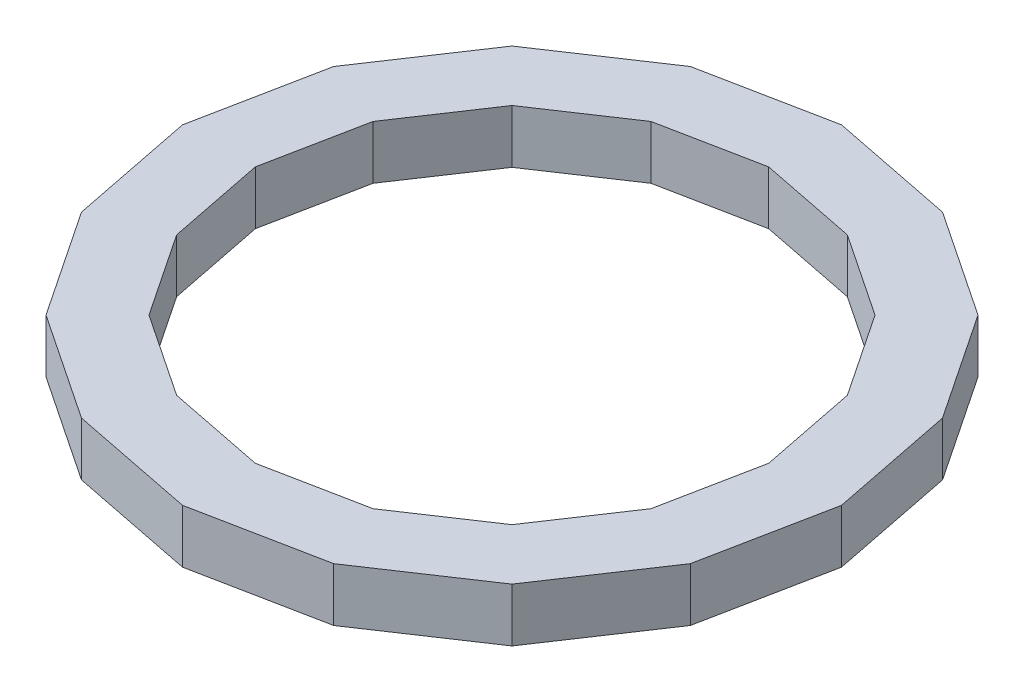
SolidWorks part; units mm, degrees
ref_plane "Front Plane" through (0, 0, 0) normal (0, 0, 1) x (1, 0, 0)
ref_plane "Top Plane" through (0, 0, 0) normal (0, 1, 0) x (1, 0, 0)
ref_plane "Right Plane" through (0, 0, 0) normal (1, 0, 0) x (0, 0, -1)
sketch "Sketch1" plane through (0, 0, 0) normal (0, 1, 0) x (1, 0, 0)
  line L0 (108.257, 44.8415) -> (84.3307, 34.9309) construction
  line L1 (117.1765, 0) -> (108.257, 44.8415)
  line L2 (108.257, 44.8415) -> (82.8563, 82.8563)
  line L3 (82.8563, 82.8563) -> (44.8415, 108.257)
  line L4 (44.8415, 108.257) -> (0, 117.1765)
  line L5 (0, 117.1765) -> (-44.8415, 108.257)
  line L6 (-44.8415, 108.257) -> (-82.8563, 82.8563)
  line L7 (-82.8563, 82.8563) -> (-108.257, 44.8415)
  line L8 (-108.257, 44.8415) -> (-117.1765, 0)
  line L9 (-117.1765, 0) -> (-108.257, -44.8415)
  line L10 (-108.257, -44.8415) -> (-82.8563, -82.8563)
  line L11 (-82.8563, -82.8563) -> (-44.8415, -108.257)
  line L12 (-44.8415, -108.257) -> (0, -117.1765)
  line L13 (0, -117.1765) -> (44.8415, -108.257)
  line L14 (44.8415, -108.257) -> (82.8563, -82.8563)
  line L15 (82.8563, -82.8563) -> (108.257, -44.8415)
  line L16 (108.257, -44.8415) -> (117.1765, 0)
  line L17 (91.2789, 0) -> (84.3307, 34.9309)
  line L18 (84.3307, 34.9309) -> (64.5439, 64.5439)
  line L19 (64.5439, 64.5439) -> (34.9309, 84.3307)
  line L20 (34.9309, 84.3307) -> (0, 91.2789)
  line L21 (0, 91.2789) -> (-34.9309, 84.3307)
  line L22 (-34.9309, 84.3307) -> (-64.5439, 64.5439)
  line L23 (-64.5439, 64.5439) -> (-84.3307, 34.9309)
  line L24 (-84.3307, 34.9309) -> (-91.2789, 0)
  line L25 (-91.2789, 0) -> (-84.3307, -34.9309)
  line L26 (-84.3307, -34.9309) -> (-64.5439, -64.5439)
  line L27 (-64.5439, -64.5439) -> (-34.9309, -84.3307)
  line L28 (-34.9309, -84.3307) -> (0, -91.2789)
  line L29 (0, -91.2789) -> (34.9309, -84.3307)
  line L30 (34.9309, -84.3307) -> (64.5439, -64.5439)
  line L31 (64.5439, -64.5439) -> (84.3307, -34.9309)
  line L32 (84.3307, -34.9309) -> (91.2789, 0)
  circle A0 centre (0, 0) radius 114.925 construction
  circle A1 centre (0, 0) radius 89.525 construction
  dimension "D1" = 25.4
  dimension "D2" = 45.72
  dimension "D3" = 101.25
extrude "Boss-Extrude1" add sketch "Sketch1" along normal blind 19.05
